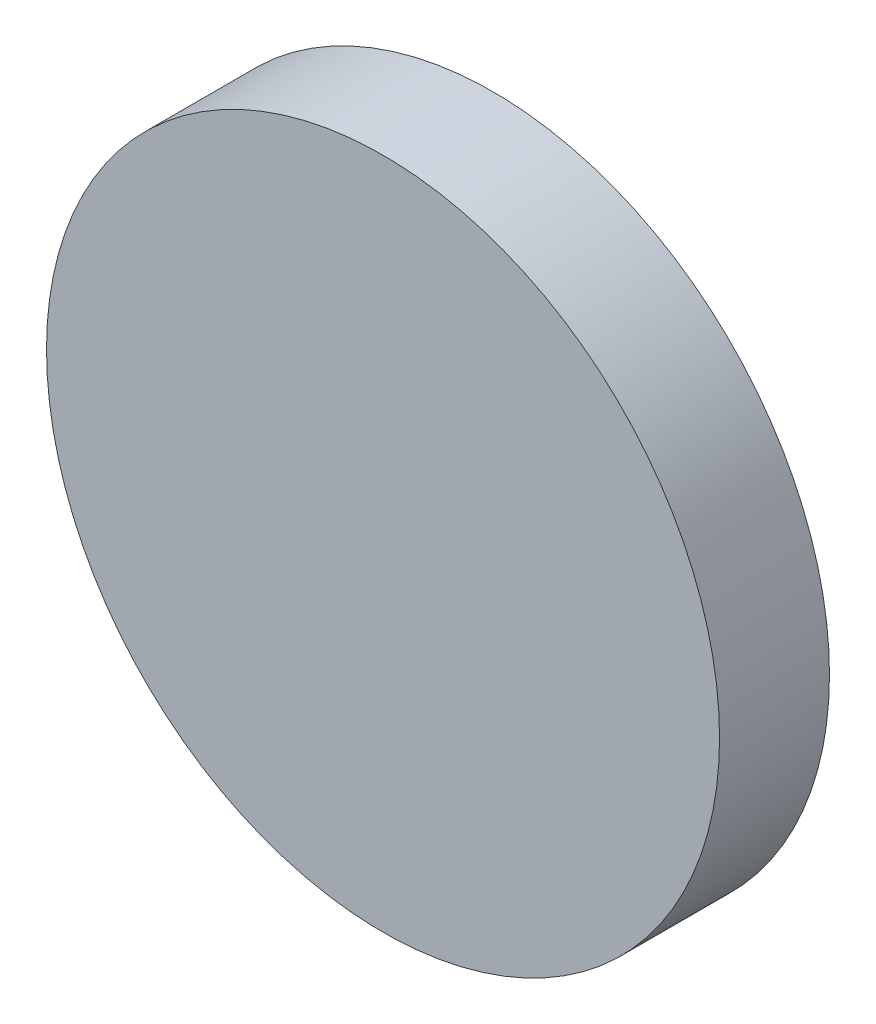
SolidWorks part; units mm, degrees
ref_plane "Plan de face" through (0, 0, 0) normal (0, 0, 1) x (1, 0, 0)
ref_plane "Plan de dessus" through (0, 0, 0) normal (0, 1, 0) x (1, 0, 0)
ref_plane "Plan de droite" through (0, 0, 0) normal (1, 0, 0) x (0, 0, -1)
sketch "Esquisse1" plane through (0, 0, 0) normal (0, 0, 1) x (1, 0, 0)
  circle A0 centre (0, 0) radius 15
  dimension "D1" = 30
extrude "Boss.-Extru.1" add sketch "Esquisse1" along normal blind 4.9
